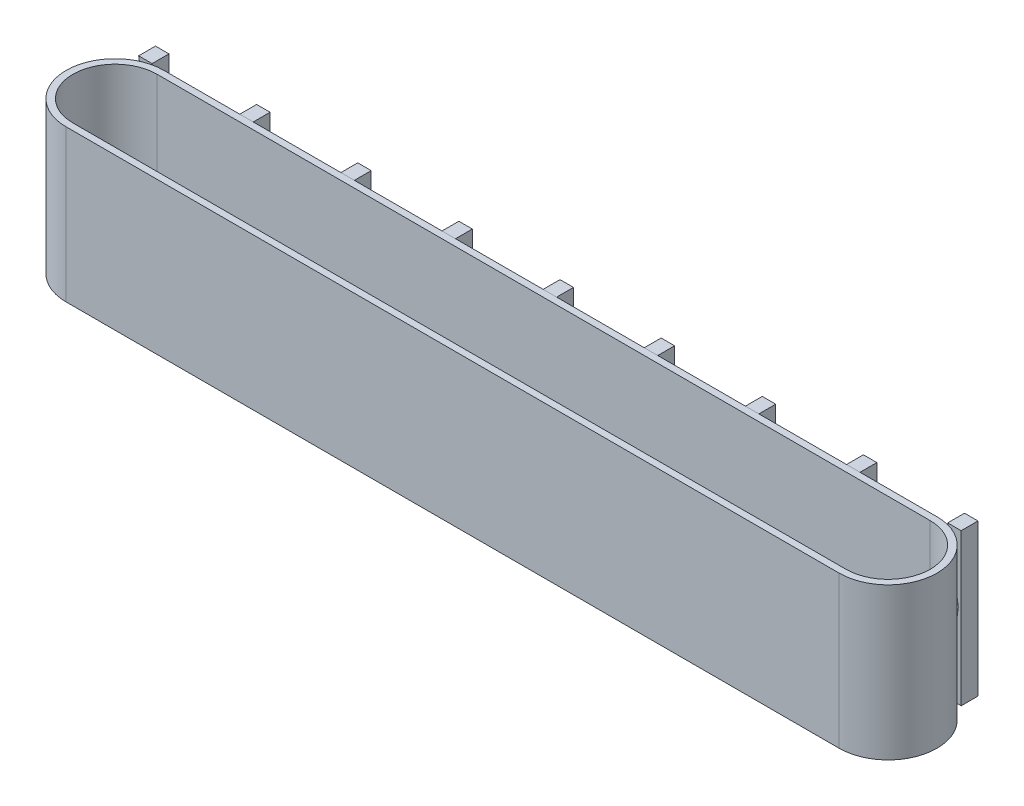
SolidWorks part; units mm, degrees
ref_plane "Alzado" through (0, 0, 0) normal (0, 0, 1) x (1, 0, 0)
ref_plane "Planta" through (0, 0, 0) normal (0, 1, 0) x (1, 0, 0)
ref_plane "Vista lateral" through (0, 0, 0) normal (1, 0, 0) x (0, 0, -1)
sketch "Croquis1" plane through (0, 0, 0) normal (0, 1, 0) x (1, 0, 0)
  line L0 (-114.67, 0) -> (114.67, 0) construction
  line L1 (-114.67, 12.5) -> (114.67, 12.5)
  line L2 (-114.67, -12.5) -> (114.67, -12.5)
  line L3 (-114.67, 0) -> (114.67, 0) construction
  line L4 (-114.67, 14.5) -> (114.67, 14.5)
  line L5 (-114.67, -14.5) -> (114.67, -14.5)
  arc A0 (-114.67, 12.5) -> (-114.67, -12.5) centre (-114.67, 0) ccw
  arc A1 (114.67, -12.5) -> (114.67, 12.5) centre (114.67, 0) ccw
  arc A2 (-114.67, 14.5) -> (-114.67, -14.5) centre (-114.67, 0) ccw
  arc A3 (114.67, -14.5) -> (114.67, 14.5) centre (114.67, 0) ccw
  point P2 (0, 0)
  point P10 (0, 0)
  dimension "D3" = 12.5
  dimension "D4" = 0
  dimension "D1" = 2
  dimension "D2" = 229.34
extrude "Saliente-Extruir1" add sketch "Croquis1" along normal blind 45
sketch "Croquis2" plane through (0, 0, -14.5) normal (0, 0, -1) x (-1, 0, 0)
  line L0 (-114.67, 45) -> (114.67, 45) construction
  line L1 (-121.8401, 45) -> (-117.8401, 45)
  line L2 (-121.8401, 45) -> (-121.8401, 0)
  line L3 (-121.8401, 0) -> (-117.8401, 0)
  line L5 (-114.67, 0) -> (114.67, 0) construction
  line L6 (-117.8401, 45) -> (-120.9961, 25)
  line L7 (-120.9961, 25) -> (-117.8401, 0)
  dimension "D1" = 4
extrude "Saliente-Extruir2" add sketch "Croquis2" along normal blind 5 separate body
pattern_linear "MatrizL1" count 9 spacing 30 along (-1, 0, 0) of "Saliente-Extruir2"
